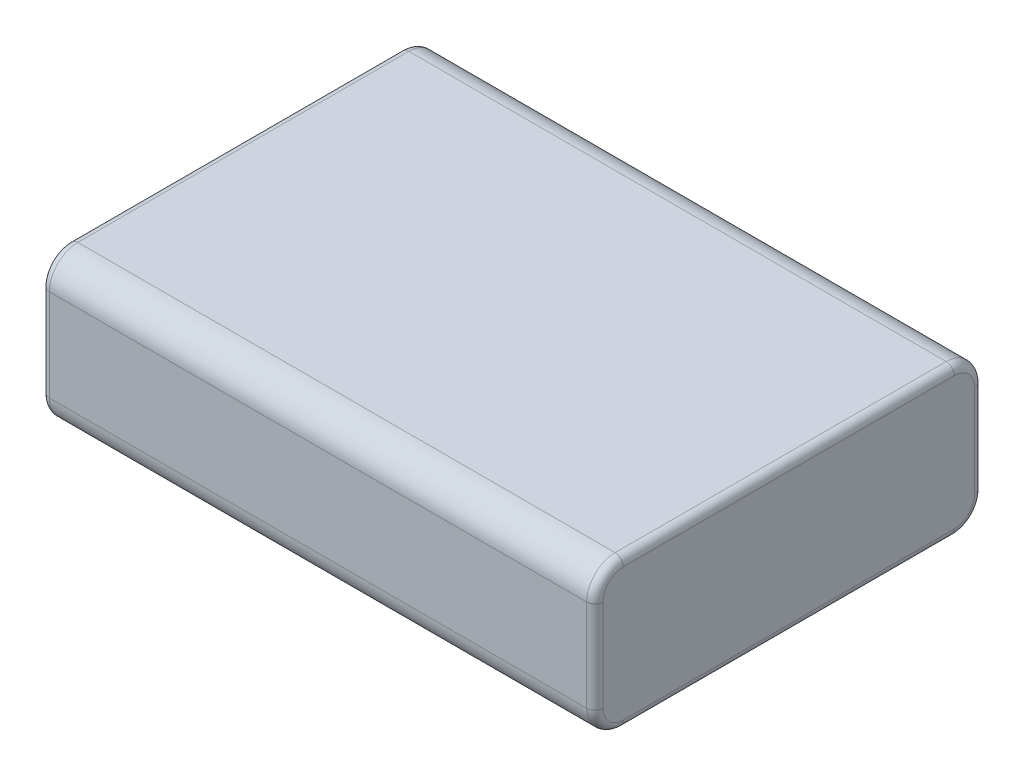
SolidWorks part; units mm, degrees
ref_plane "Front Plane" through (0, 0, 0) normal (0, 0, 1) x (1, 0, 0)
ref_plane "Top Plane" through (0, 0, 0) normal (0, 1, 0) x (1, 0, 0)
ref_plane "Right Plane" through (0, 0, 0) normal (1, 0, 0) x (0, 0, -1)
sketch "Sketch1" plane through (0, 0, 0) normal (1, 0, 0) x (0, 0, -1)
  line L1 (-23.825, 9.15) -> (23.825, 9.15)
  line L2 (-23.825, 9.15) -> (-23.825, -9.15)
  line L3 (-23.825, -9.15) -> (23.825, -9.15)
  line L4 (23.825, 9.15) -> (23.825, -9.15)
  line L5 (-23.825, 9.15) -> (23.825, -9.15) construction
  line L6 (-23.825, -9.15) -> (23.825, 9.15) construction
  point P0 (0, 0)
  dimension "D1" = 18.3
  dimension "D2" = 47.65
extrude "Boss-Extrude1" add sketch "Sketch1" along normal mid plane 68
fillet "Fillet1" radius 3.5 4 edges at (0, -9.15, 23.825) (0, -9.15, -23.825) (0, 9.15, 23.825) (0, 9.15, -23.825)
fillet "Fillet2" radius 1 16 edges at (-34, 8.1249, -22.7999) (-34, 0, -23.825) (-34, -8.1249, -22.7999) (-34, -9.15, 0) (-34, -8.1249, 22.7999) (-34, 0, 23.825) (-34, 8.1249, 22.7999) (34, 8.1249, -22.7999) (34, 0, -23.825) (34, -8.1249, -22.7999) (34, -9.15, 0) (34, -8.1249, 22.7999) (34, 0, 23.825) (34, 8.1249, 22.7999) (-34, 9.15, 0) (34, 9.15, 0)
